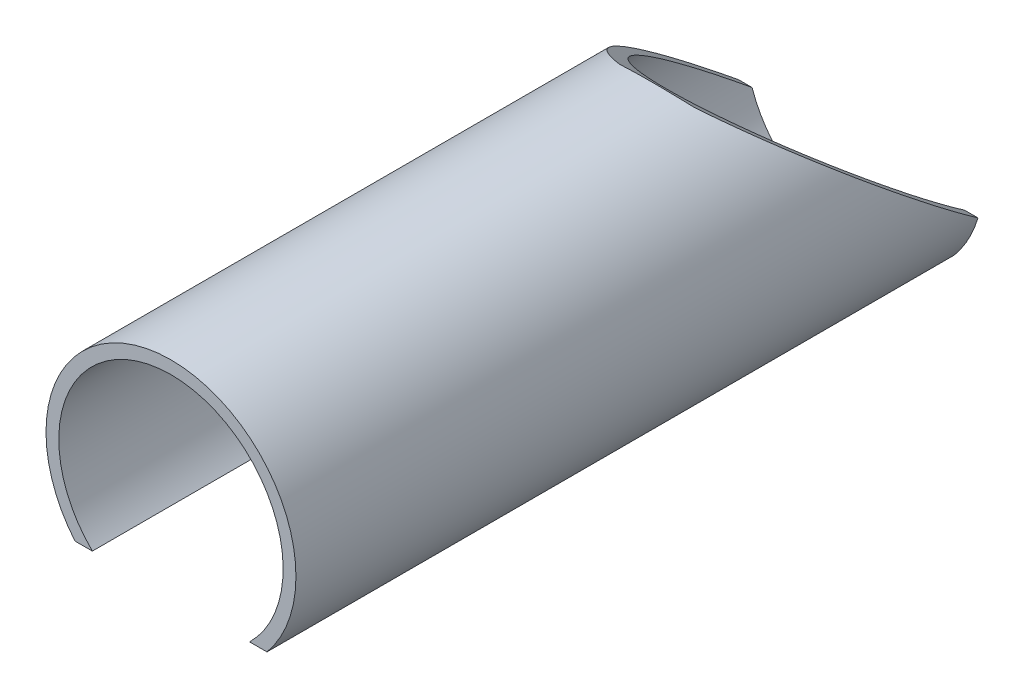
SolidWorks part; units mm, degrees
ref_plane "Front Plane" through (0, 0, 0) normal (0, 0, 1) x (1, 0, 0)
ref_plane "Top Plane" through (0, 0, 0) normal (0, 1, 0) x (1, 0, 0)
ref_plane "Right Plane" through (0, 0, 0) normal (1, 0, 0) x (0, 0, -1)
sketch "Sketch1" plane through (0, 0, 0) normal (0, 0, 1) x (1, 0, 0)
  circle A0 centre (0, 0) radius 16
  dimension "D1" = 32
extrude "Boss-Extrude1" add sketch "Sketch1" along normal blind 88 contours A0
sketch "Sketch2" plane through (0, 0, 88) normal (0, 0, 1) x (1, 0, 0)
  circle A0 centre (0, 0) radius 14.3605
extrude "Cut-Extrude1" cut sketch "Sketch2" against normal blind 88
sketch "Sketch3" plane through (0, 0, 88) normal (0, 0, 1) x (1, 0, 0)
  line L1 (-19.6651, -17.76) -> (21.8398, -17.76)
  line L2 (-19.6651, -17.76) -> (-19.6651, -10.2435)
  line L3 (-19.6651, -10.2435) -> (21.8398, -10.2435)
  line L4 (21.8398, -17.76) -> (21.8398, -10.2435)
extrude "Cut-Extrude2" cut sketch "Sketch3" against normal blind 88 contours L4 L3 L2 L1
sketch "Sketch4" plane through (0, 0, 0) normal (1, 0, 0) x (0, 0, -1)
  line L0 (9.0633, -11.589) -> (-25.8044, 15.2827)
  line L1 (-30.2074, 20.4329) -> (-25.8044, 15.2827)
  line L2 (-30.2074, 20.4329) -> (5.0892, 19.3117)
  line L3 (5.0892, 19.3117) -> (9.0633, -11.589)
extrude "Cut-Extrude3" cut sketch "Sketch4" against normal through all both and the other way through all
